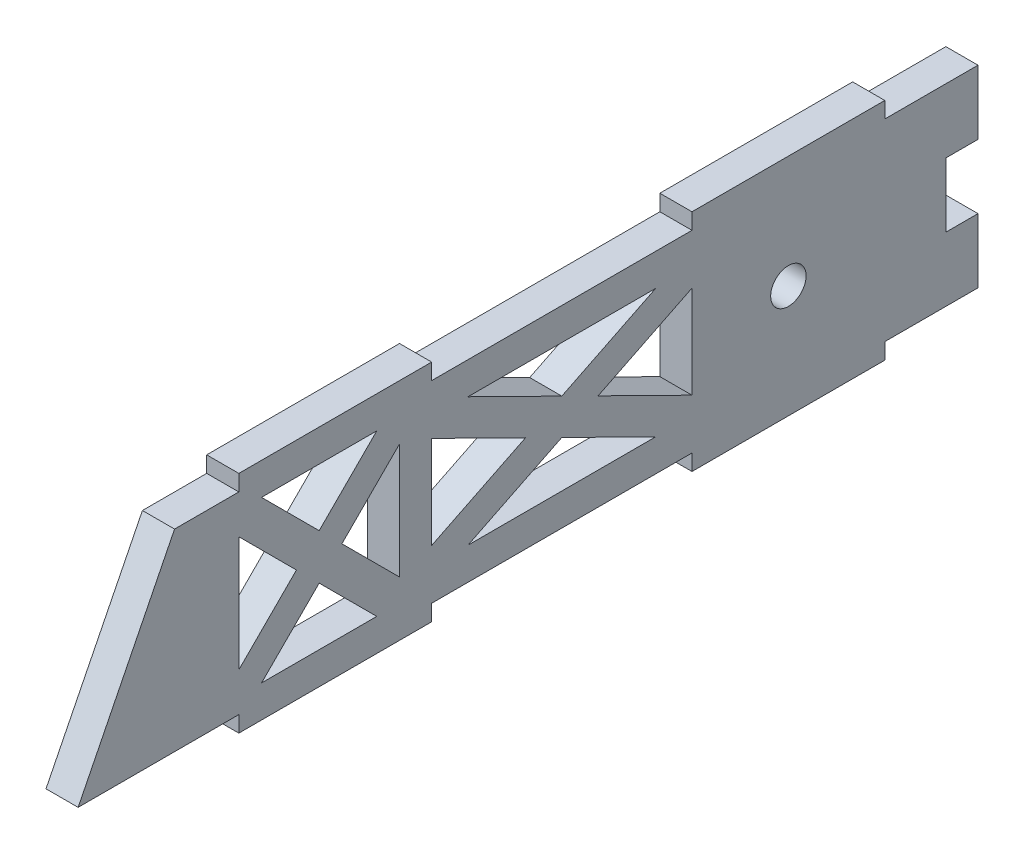
SolidWorks part; units mm, degrees
material "7050-T73510"
ref_plane "Front Plane" through (0, 0, 0) normal (0, 0, 1) x (1, 0, 0)
ref_plane "Top Plane" through (0, 0, 0) normal (0, 1, 0) x (1, 0, 0)
ref_plane "Right Plane" through (0, 0, 0) normal (1, 0, 0) x (0, 0, -1)
sketch "Sketch1" plane through (0, 0, 0) normal (1, 0, 0) x (0, 0, -1)
  line L1 (-177.8, -38.1) -> (177.8, -38.1)
  line L2 (-177.8, -38.1) -> (-177.8, 38.1)
  line L3 (-177.8, 38.1) -> (177.8, 38.1)
  line L4 (177.8, -38.1) -> (177.8, 38.1)
  line L5 (-177.8, -38.1) -> (177.8, 38.1) construction
  line L6 (-177.8, 38.1) -> (177.8, -38.1) construction
  point P0 (0, 0)
  dimension "D1" = 355.6
  dimension "D2" = 76.2
extrude "Boss-Extrude1" add sketch "Sketch1" along normal blind 12.7
sketch "Sketch2" plane through (12.7, 0, 0) normal (1, 0, 0) x (0, 0, -1)
  line L0 (-177.8, -38.1) -> (-139.7, 38.1)
  line L1 (177.8, 38.1) -> (-177.8, 38.1) construction
  dimension "D1" = 38.1
extrude "Cut-Extrude1" cut sketch "Sketch2" against normal through all and the other way through all
sketch "Sketch3" plane through (0, 0, 0) normal (-1, 0, 0) x (0, 0, 1)
  line L0 (177.8, -38.1) -> (-177.8, -38.1) construction
  line L1 (-140.97, -38.1) -> (-64.77, -38.1)
  line L2 (-140.97, -38.1) -> (-140.97, -44.45)
  line L3 (-140.97, -44.45) -> (-64.77, -44.45)
  line L4 (-64.77, -38.1) -> (-64.77, -44.45)
  line L5 (-177.8, -38.1) -> (-177.8, 38.1) construction
  line L6 (38.1, -38.1) -> (114.3, -38.1)
  line L7 (38.1, -38.1) -> (38.1, -44.45)
  line L8 (38.1, -44.45) -> (114.3, -44.45)
  line L9 (114.3, -38.1) -> (114.3, -44.45)
  line L10 (-177.8, 38.1) -> (139.7, 38.1) construction
  line L11 (-140.97, 38.1) -> (-64.77, 38.1)
  line L12 (-140.97, 38.1) -> (-140.97, 44.45)
  line L13 (-140.97, 44.45) -> (-64.77, 44.45)
  line L14 (-64.77, 38.1) -> (-64.77, 44.45)
  line L16 (38.1, 38.1) -> (114.3, 38.1)
  line L17 (38.1, 38.1) -> (38.1, 44.45)
  line L18 (38.1, 44.45) -> (114.3, 44.45)
  line L19 (114.3, 38.1) -> (114.3, 44.45)
  dimension "D1" = 76.2
  dimension "D2" = 6.35
  dimension "D3" = 76.2
  dimension "D4" = 6.35
  dimension "D5" = 36.83
  dimension "D6" = 215.9
  dimension "D7" = 76.2
  dimension "D8" = 6.35
  dimension "D9" = 6.35
  dimension "D10" = 76.2
extrude "Boss-Extrude2" add sketch "Sketch3" against normal blind 12.7
sketch "Sketch4" plane through (0, 0, 0) normal (-1, 0, 0) x (0, 0, 1)
  line L0 (-177.8, -38.1) -> (-177.8, 38.1) construction
  line L1 (-177.8, 12.7) -> (-165.1, 12.7)
  line L2 (-177.8, 12.7) -> (-177.8, -12.7)
  line L3 (-177.8, -12.7) -> (-165.1, -12.7)
  line L4 (-165.1, 12.7) -> (-165.1, -12.7)
  line L5 (-140.97, -38.1) -> (-177.8, -38.1) construction
  line L6 (-177.8, 38.1) -> (-140.97, 38.1) construction
  dimension "D1" = 25.4
  dimension "D2" = 25.4
  dimension "D3" = 12.7
extrude "Cut-Extrude2" cut sketch "Sketch4" against normal through all
sketch "Sketch5" plane through (0, 0, 0) normal (-1, 0, 0) x (0, 0, 1)
  line L0 (-165.1, -12.7) -> (-165.1, 12.7) construction
  line L1 (-140.97, -38.1) -> (-177.8, -38.1) construction
  circle A0 centre (-102.87, 0) radius 7
  dimension "D1" = 62.23
  dimension "D3" = 14
  dimension "D2" = 38.1
extrude "Cut-Extrude3" cut sketch "Sketch5" against normal through all
sketch "Sketch6" plane through (0, 0, 0) normal (-1, 0, 0) x (0, 0, 1)
  line L0 (38.1, -38.1) -> (-64.77, -38.1) construction
  line L1 (-64.77, 25.4) -> (38.1, 25.4)
  line L2 (-64.77, 25.4) -> (-64.77, -25.4)
  line L3 (-64.77, -25.4) -> (38.1, -25.4)
  line L4 (38.1, 25.4) -> (38.1, -25.4)
  line L5 (-64.77, 38.1) -> (38.1, 38.1) construction
  line L6 (38.1, 44.45) -> (38.1, 38.1) construction
  line L7 (-64.77, 38.1) -> (-64.77, 44.45) construction
  line L8 (-64.77, 25.4) -> (38.1, -25.4) construction
  line L9 (-64.77, -25.4) -> (38.1, 25.4) construction
  line L10 (-50.4288, -25.4) -> (-13.335, -7.0821)
  line L11 (23.7588, 25.4) -> (-13.335, 7.0821)
  line L12 (-50.4288, 25.4) -> (-13.335, 7.0821)
  line L13 (23.7588, -25.4) -> (-13.335, -7.0821)
  line L14 (1.0062, 0) -> (38.1, 18.3179)
  line L15 (-27.6762, 0) -> (-64.77, 18.3179)
  line L16 (1.0062, 0) -> (38.1, -18.3179)
  line L17 (-27.6762, 0) -> (-64.77, -18.3179)
  line L18 (38.1, -44.45) -> (114.3, -44.45) construction
  line L19 (50.8, 31.75) -> (114.3, 31.75)
  line L20 (50.8, 31.75) -> (50.8, -31.75)
  line L21 (50.8, -31.75) -> (114.3, -31.75)
  line L22 (114.3, 31.75) -> (114.3, -31.75)
  line L23 (114.3, 44.45) -> (38.1, 44.45) construction
  line L26 (114.3, 38.1) -> (114.3, 44.45) construction
  line L28 (50.8, -31.75) -> (114.3, 31.75) construction
  line L29 (114.3, -31.75) -> (50.8, 31.75) construction
  line L30 (59.7803, -31.75) -> (114.3, 22.7697)
  line L31 (50.8, -22.7697) -> (105.3197, 31.75)
  line L32 (114.3, -22.7697) -> (59.7803, 31.75)
  line L33 (105.3197, -31.75) -> (50.8, 22.7697)
  point P36 (114.3, 41.275)
  dimension "D1" = 12.7
  dimension "D2" = 12.7
  dimension "D3" = 12.7
  dimension "D4" = 12.7
  dimension "D5" = 12.7
  dimension "D6" = 12.7
  dimension "D7" = 12.7
  dimension "D8" = 0
  dimension "D9" = 12.7
  dimension "D10" = 12.7
extrude "Cut-Extrude4" cut sketch "Sketch6" against normal through all contours L3 L13 L10 | L17 L15 L2 | L1 L12 L11 | L14 L16 L4 | L21 L33 L30 | L32 L22 L30 | L31 L33 L20 | L32 L31 L19
